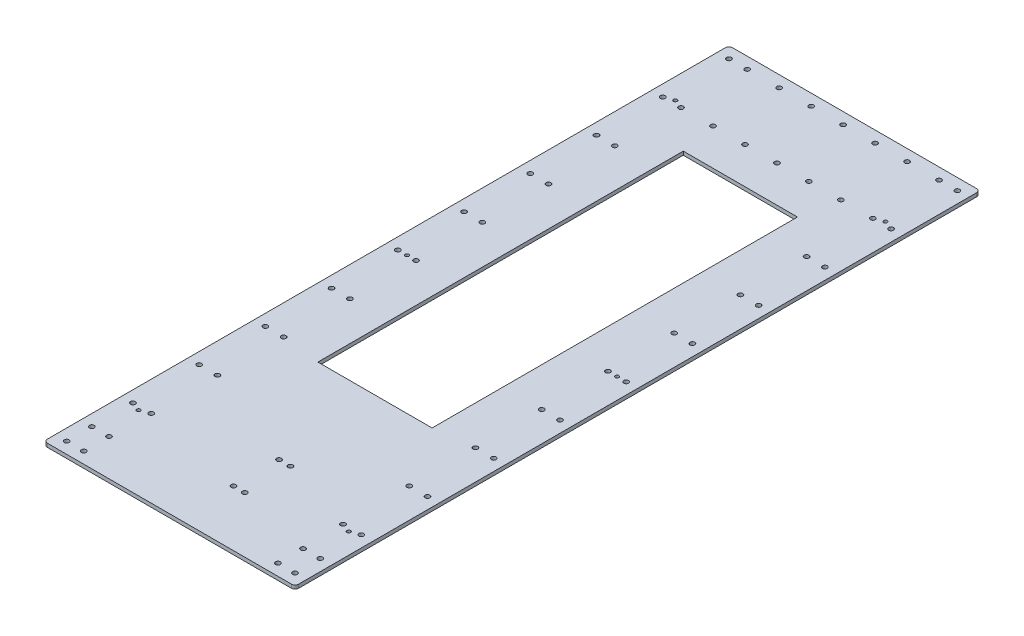
SolidWorks part; units mm, degrees
ref_plane "Front Plane" through (0, 0, 0) normal (0, 0, 1) x (1, 0, 0)
ref_plane "Top Plane" through (0, 0, 0) normal (0, 1, 0) x (1, 0, 0)
ref_plane "Right Plane" through (0, 0, 0) normal (1, 0, 0) x (0, 0, -1)
sketch "Sketch1" plane through (0, 0, 0) normal (0, 1, 0) x (1, 0, 0)
  line L0 (92, 300) -> (92, -300) construction
  line L1 (-110, -300) -> (110, -300)
  line L2 (-110, -300) -> (-110, 300)
  line L3 (-110, 300) -> (110, 300)
  line L4 (110, -300) -> (110, 300)
  line L5 (-110, -300) -> (110, 300) construction
  line L6 (-110, 300) -> (110, -300) construction
  line L7 (-110, 0) -> (110, 0) construction
  line L8 (0, 300) -> (0, -300) construction
  line L9 (84, 290) -> (56, 290) construction
  line L10 (66.9634, -279) -> (106.2482, -279) construction
  line L11 (-50, -120) -> (50, -120)
  line L12 (-50, -120) -> (-50, 200)
  line L13 (-50, 200) -> (50, 200)
  line L14 (50, -120) -> (50, 200)
  line L15 (-28, -231) -> (24.6506, -231) construction
  circle A0 centre (100, 290) radius 2.1
  circle A1 centre (100, 232) radius 2.1
  circle A2 centre (100, 174) radius 2.1
  circle A3 centre (100, 116) radius 2.1
  circle A4 centre (100, 58) radius 2.1
  circle A5 centre (100, 0) radius 2.1
  circle A6 centre (100, -58) radius 2.1
  circle A7 centre (100, -116) radius 2.1
  circle A8 centre (100, -174) radius 2.1
  circle A9 centre (100, -232) radius 2.1
  circle A10 centre (100, -290) radius 2.1
  circle A11 centre (84, -290) radius 2.1 construction
  circle A12 centre (84, -232) radius 2.1
  circle A13 centre (84, -174) radius 2.1
  circle A14 centre (84, -116) radius 2.1
  circle A15 centre (84, -58) radius 2.1
  circle A16 centre (84, 0) radius 2.1
  circle A17 centre (84, 58) radius 2.1
  circle A18 centre (84, 116) radius 2.1
  circle A19 centre (84, 174) radius 2.1
  circle A20 centre (84, 232) radius 2.1
  circle A21 centre (84, 290) radius 2.1
  circle A22 centre (92, 0) radius 1.6
  circle A23 centre (92, 235) radius 1.6
  circle A24 centre (92, -235) radius 1.6
  circle A25 centre (-92, 235) radius 1.6
  circle A26 centre (-84, 290) radius 2.1
  circle A27 centre (-84, 232) radius 2.1
  circle A28 centre (-84, 174) radius 2.1
  circle A29 centre (-84, 116) radius 2.1
  circle A30 centre (-100, 116) radius 2.1
  circle A31 centre (-100, 174) radius 2.1
  circle A32 centre (-100, 232) radius 2.1
  circle A33 centre (-100, 290) radius 2.1
  circle A34 centre (-92, -235) radius 1.6
  circle A35 centre (-92, 0) radius 1.6
  circle A36 centre (-84, 58) radius 2.1
  circle A37 centre (-84, 0) radius 2.1
  circle A38 centre (-84, -58) radius 2.1
  circle A39 centre (-84, -116) radius 2.1
  circle A40 centre (-84, -174) radius 2.1
  circle A41 centre (-84, -232) radius 2.1
  circle A42 centre (-84, -290) radius 2.1 construction
  circle A43 centre (-100, -290) radius 2.1
  circle A44 centre (-100, -232) radius 2.1
  circle A45 centre (-100, -174) radius 2.1
  circle A46 centre (-100, -116) radius 2.1
  circle A47 centre (-100, -58) radius 2.1
  circle A48 centre (-100, 0) radius 2.1
  circle A49 centre (-100, 58) radius 2.1
  circle A50 centre (56, 290) radius 2.1
  circle A51 centre (28, 290) radius 2.1
  circle A52 centre (0, 290) radius 2.1
  circle A53 centre (-28, 290) radius 2.1
  circle A54 centre (-56, 290) radius 2.1
  circle A55 centre (56, 232) radius 2.1
  circle A56 centre (28, 232) radius 2.1
  circle A57 centre (0, 232) radius 2.1
  circle A58 centre (-28, 232) radius 2.1
  circle A59 centre (-56, 232) radius 2.1
  circle A61 centre (84, 232) radius 2.1 [skipped]
  circle A62 centre (85, -290) radius 2.1
  circle A63 centre (85, -268) radius 2.1
  circle A64 centre (100, -268) radius 2.1
  circle A65 centre (-85, -290) radius 2.1
  circle A66 centre (-100, -268) radius 2.1
  circle A67 centre (-85, -268) radius 2.1
  circle A68 centre (17, -251) radius 2.1
  circle A69 centre (7, -251) radius 2.1
  circle A70 centre (17, -211) radius 2.1
  circle A71 centre (7, -211) radius 2.1
  point P0 (0, 0)
  point P112 (0, 0)
  dimension "D5" = 4.2
  dimension "D8" = 3.2
  dimension "D9" = 3.2
  dimension "D19" = 4.2
  dimension "D23" = 4.2
  dimension "D25" = 4.2
  dimension "D1" = 600
  dimension "D2" = 220
  dimension "D3" = 18
  dimension "D4" = 8
  dimension "D6" = 10
  dimension "D10" = 235
  dimension "D13" = 28
  dimension "D14" = 58
  dimension "D15" = 100
  dimension "D16" = 200
  dimension "D17" = 120
  dimension "D18" = 50
  dimension "D20" = 15
  dimension "D21" = 11
  dimension "D24" = 20
  dimension "D26" = 10
  dimension "D27" = 127
  dimension "D22" = 69
  dimension "D7" = 11
  dimension "D11" = 6
  dimension "D12" = 2
extrude "Boss-Extrude1" add sketch "Sketch1" along normal blind 3.175
fillet "Fillet1" radius 3.2 4 edges at (110, 1.5875, 300) (-110, 1.5875, 300) (-110, 1.5875, -300) (110, 1.5875, -300)
equation "\"m4\"= 4.2"
equation "\"m3\"=3.2"
equation "\"D5@Sketch1\"=\"m4\""
equation "\"width\"= 220"
equation "\"height\"= 600"
equation "\"D2@Sketch1\"=\"width\""
equation "\"D1@Sketch1\"=\"height\""
equation "\"D8@Sketch1\"=\"m3\""
equation "\"D9@Sketch1\"=\"m3\""
equation "\"D19@Sketch1\"=\"m4\""
equation "\"D23@Sketch1\"=\"m4\""
equation "\"D25@Sketch1\"=\"m4\"'"
